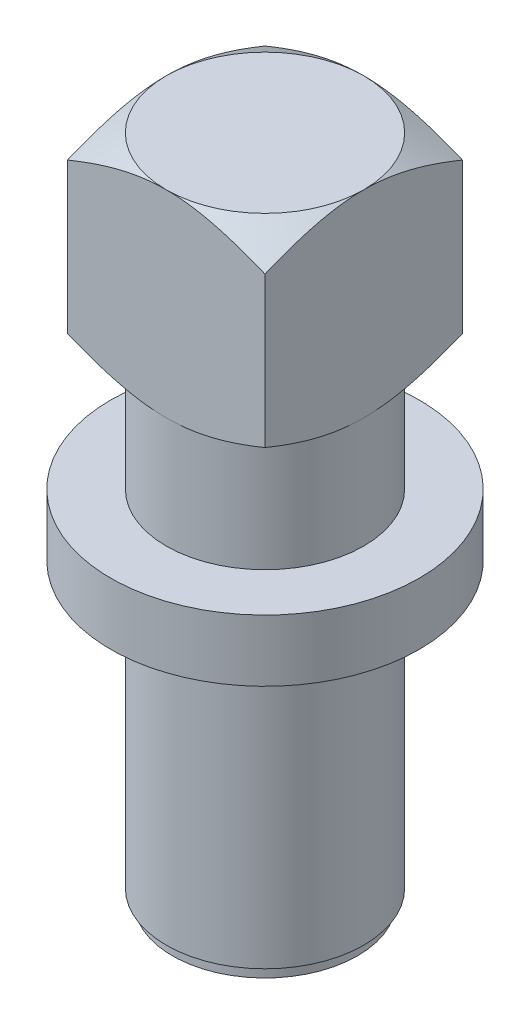
SolidWorks part; units mm, degrees
material "Wrought Stainless Steel"
ref_plane "Front Plane" through (0, 0, 0) normal (0, 0, 1) x (1, 0, 0)
ref_plane "Top Plane" through (0, 0, 0) normal (0, 1, 0) x (1, 0, 0)
ref_plane "Right Plane" through (0, 0, 0) normal (1, 0, 0) x (0, 0, -1)
sketch "Sketch1" plane through (0, 0, 0) normal (0, 0, 1) x (1, 0, 0)
  line L0 (0, 0) -> (-7.5, 0)
  line L1 (-7.5, 0) -> (-7.5, 1)
  line L2 (-7.5, 1) -> (-8, 1)
  line L3 (-8, 1) -> (-8, 24)
  line L4 (-8, 24) -> (-12.5, 24)
  line L5 (-12.5, 24) -> (-12.5, 29)
  line L6 (-12.5, 29) -> (-8, 29)
  line L7 (-8, 29) -> (-8, 38)
  line L8 (-8, 38) -> (0, 38)
  line L9 (0, 38) -> (0, 0)
  dimension "D1" = 7.5
  dimension "D2" = 8
  dimension "D3" = 5
  dimension "D4" = 24
  dimension "D5" = 12.5
  dimension "D6" = 9
  dimension "D7" = 1
revolve "Revolve1" add sketch "Sketch1" angle 360 about L9
sketch "Sketch2" plane through (0, 38, 0) normal (0, 1, 0) x (1, 0, 0)
  line L1 (-8, 8) -> (8, 8)
  line L2 (-8, 8) -> (-8, -8)
  line L3 (-8, -8) -> (8, -8)
  line L4 (8, 8) -> (8, -8)
  line L5 (-8, 8) -> (8, -8) construction
  line L6 (-8, -8) -> (8, 8) construction
  point P0 (0, 0)
  dimension "D1" = 16
  dimension "D2" = 16
extrude "Boss-Extrude1" add sketch "Sketch2" along normal blind 16
sketch "Sketch3" plane through (0, 54, 0) normal (0, 1, 0) x (1, 0, 0)
  line L0 (-8, -8) -> (8, -8) construction
  circle A0 centre (0, 0) radius 8
extrude "Cut-Extrude1" cut sketch "Sketch3" against normal through all draft 60 flip side to cut contours A0
sketch "Sketch4" plane through (0, 38, 0) normal (0, -1, 0) x (1, 0, 0)
  circle A0 centre (0, 0) radius 8 construction
  circle A1 centre (0, 0) radius 8
extrude "Cut-Extrude2" cut sketch "Sketch4" against normal through all draft 60 flip side to cut
